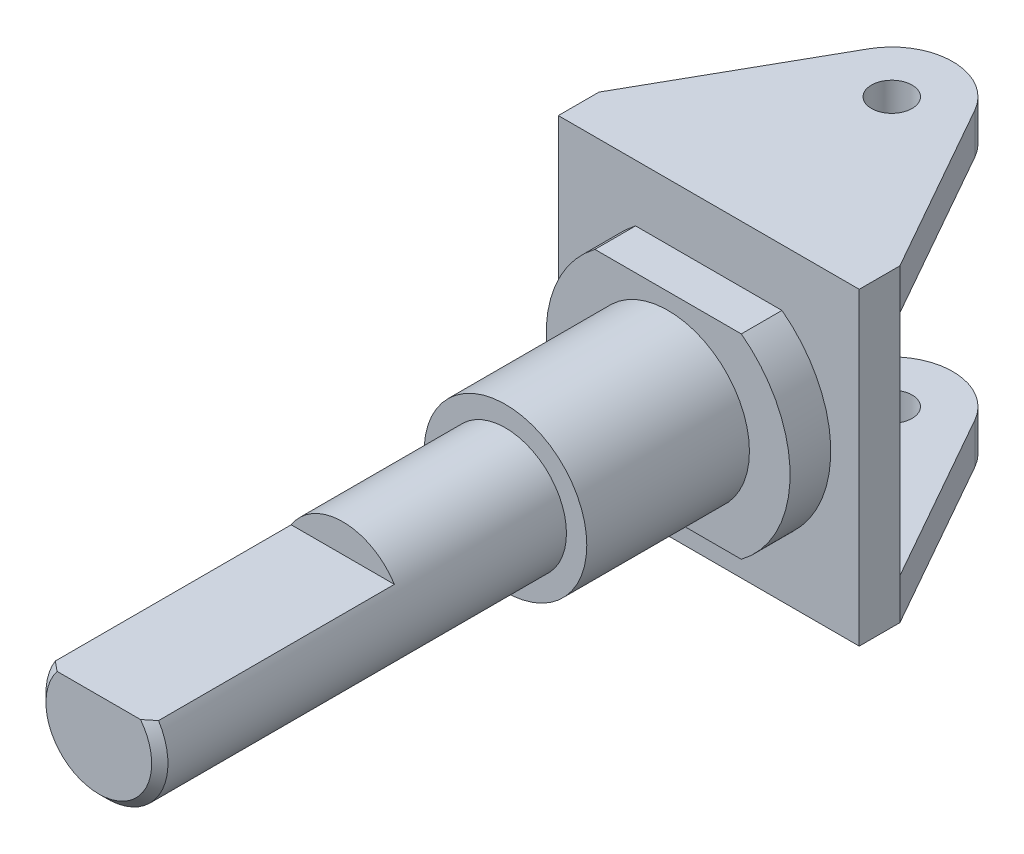
SolidWorks part; units mm, degrees
ref_plane "Front Plane" through (0, 0, 0) normal (0, 0, 1) x (1, 0, 0)
ref_plane "Top Plane" through (0, 0, 0) normal (0, 1, 0) x (1, 0, 0)
ref_plane "Right Plane" through (0, 0, 0) normal (1, 0, 0) x (0, 0, -1)
sketch "Sketch1" plane through (0, 0, 0) normal (0, 0, 1) x (1, 0, 0)
  line L0 (-37, 28) -> (-37, -28)
  line L1 (-37, -28) -> (37, -28)
  line L2 (37, -28) -> (37, 28)
  line L3 (37, 28) -> (-37, 28)
extrude "Boss-Extrude1" add sketch "Sketch1" against normal blind 10
sketch "Sketch2" plane through (0, -28, 0) normal (0, -1, 0) x (1, 0, 0)
  line L0 (-37, 0) -> (37, 0)
  line L1 (37, 0) -> (37, -10)
  line L2 (37, -10) -> (13.0601, -52.3779)
  line L3 (-13.0601, -52.3779) -> (-37, -10)
  line L4 (-37, -10) -> (-37, 0)
  arc A0 (13.0601, -52.3779) -> (-13.0601, -52.3779) centre (0, -45) cw
extrude "Boss-Extrude2" add sketch "Sketch2" along normal blind 10
sketch "Sketch3" plane through (0, 28, 0) normal (0, 1, 0) x (-1, 0, 0)
  line L0 (-37, 0) -> (37, 0)
  line L1 (37, 0) -> (37, -10)
  line L2 (37, -10) -> (13.0601, -52.3779)
  line L3 (-13.0601, -52.3779) -> (-37, -10)
  line L4 (-37, -10) -> (-37, 0)
  arc A0 (13.0601, -52.3779) -> (-13.0601, -52.3779) centre (0, -45) cw
extrude "Boss-Extrude3" add sketch "Sketch3" along normal blind 10
sketch "Sketch4" plane through (0, 0, 0) normal (0, 0, 1) x (1, 0, 0)
  line L0 (18, -24) -> (-18, -24)
  line L1 (-18, 24) -> (18, 24)
  arc A0 (18, 24) -> (18, -24) centre (0, 0) cw
  arc A1 (-18, -24) -> (-18, 24) centre (0, 0) cw
extrude "Boss-Extrude4" add sketch "Sketch4" along normal blind 10
sketch "Sketch5" plane through (0, 0, 10) normal (0, 0, 1) x (1, 0, 0)
  circle A0 centre (0, 0) radius 20
extrude "Boss-Extrude5" add sketch "Sketch5" along normal blind 40
sketch "Sketch6" plane through (0, 0, 50) normal (0, 0, 1) x (1, 0, 0)
  circle A0 centre (0, 0) radius 15
extrude "Boss-Extrude6" add sketch "Sketch6" along normal blind 100
sketch "Sketch7" plane through (0, 0, 150) normal (0, 0, 1) x (1, 0, 0)
  line L0 (-12.6886, 8) -> (12.6886, 8)
  arc A0 (12.6886, 8) -> (-12.6886, 8) centre (0, 0) ccw
extrude "Cut-Extrude1" cut sketch "Sketch7" against normal blind 60
hole_wizard "Ø10.0 (10) Diameter Hole1" positions "Sketch9" profile "Sketch8" hole size "Ø10.0" standard "ANSI Metric"
sketch "Sketch9" plane through (0, -38, 0) normal (0, -1, 0) x (-1, 0, 0)
  point P0 (0, 45)
sketch "Sketch8" plane through (0, -38, -45) normal (1, 0, 0) x (0, 0, -1)
  line L0 (0, 0) -> (0, 10)
  line L1 (0, 10) -> (5, 10)
  line L2 (5, 10) -> (5, 0)
  line L5 (5, 0) -> (0, 0)
  line L11 (0, -6.35) -> (0, 107.95) construction
  dimension "Thru Hole Dia." = 10
  dimension "Thru Hole Depth" = 10
hole_wizard "Ø10.0 (10) Diameter Hole2" positions "Sketch11" profile "Sketch10" hole size "Ø10.0" standard "ANSI Metric"
sketch "Sketch11" plane through (0, 38, 0) normal (0, 1, 0) x (1, 0, 0)
  point P0 (0, 45)
sketch "Sketch10" plane through (0, 38, -45) normal (1, 0, 0) x (0, 0, 1)
  line L0 (0, 0) -> (0, 76)
  line L1 (0, 76) -> (5, 76)
  line L2 (5, 76) -> (5, 0)
  line L5 (5, 0) -> (0, 0)
  line L11 (0, -6.35) -> (0, 107.95) construction
  dimension "Thru Hole Dia." = 10
  dimension "Thru Hole Depth" = 76
chamfer "Chamfer1" distance 2 angle 45 1 edges at (0, -15, 150)
